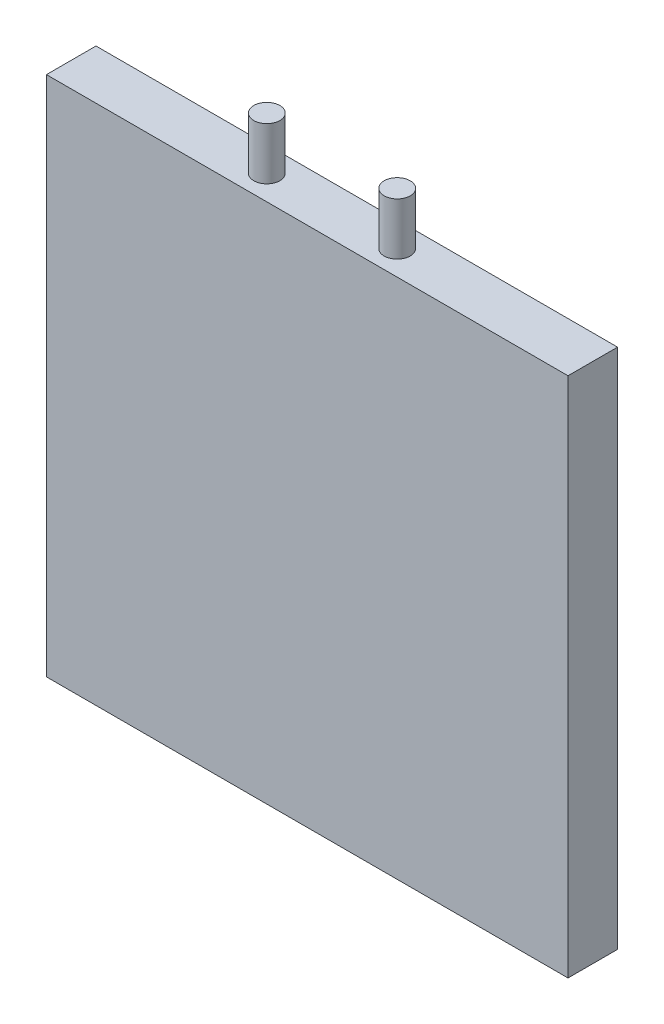
SolidWorks part; units mm, degrees
ref_plane "前视基准面" through (0, 0, 0) normal (0, 0, 1) x (1, 0, 0)
ref_plane "上视基准面" through (0, 0, 0) normal (0, 1, 0) x (1, 0, 0)
ref_plane "右视基准面" through (0, 0, 0) normal (1, 0, 0) x (0, 0, -1)
sketch "草图1" plane through (0, 0, 0) normal (0, 0, 1) x (1, 0, 0)
  line L1 (-20, 20) -> (20, 20)
  line L2 (-20, 20) -> (-20, -20)
  line L3 (-20, -20) -> (20, -20)
  line L4 (20, 20) -> (20, -20)
  line L5 (-20, 20) -> (20, -20) construction
  line L6 (-20, -20) -> (20, 20) construction
  point P0 (0, 0)
  dimension "D1" = 40
  dimension "D2" = 40
extrude "凸台-拉伸1" add sketch "草图1" along normal blind 3.8
sketch "草图3" plane through (0, 20, 0) normal (0, 1, 0) x (1, 0, 0)
  line L0 (20, -3.8) -> (20, 0) construction
  line L1 (20, -3.8) -> (-20, -3.8) construction
  circle A0 centre (5, -1.9) radius 1
  dimension "D1" = 2
  dimension "D2" = 15
  dimension "D3" = 1.9
extrude "凸台-拉伸3" add sketch "草图3" along normal blind 4
sketch "草图4" plane through (0, 20, 0) normal (0, 1, 0) x (1, 0, 0)
  line L0 (-20, -3.8) -> (-20, 0) construction
  line L1 (20, -3.8) -> (-20, -3.8) construction
  circle A0 centre (-5, -1.9) radius 1
  dimension "D1" = 2
  dimension "D2" = 15
  dimension "D3" = 1.9
extrude "凸台-拉伸4" add sketch "草图4" along normal blind 4
